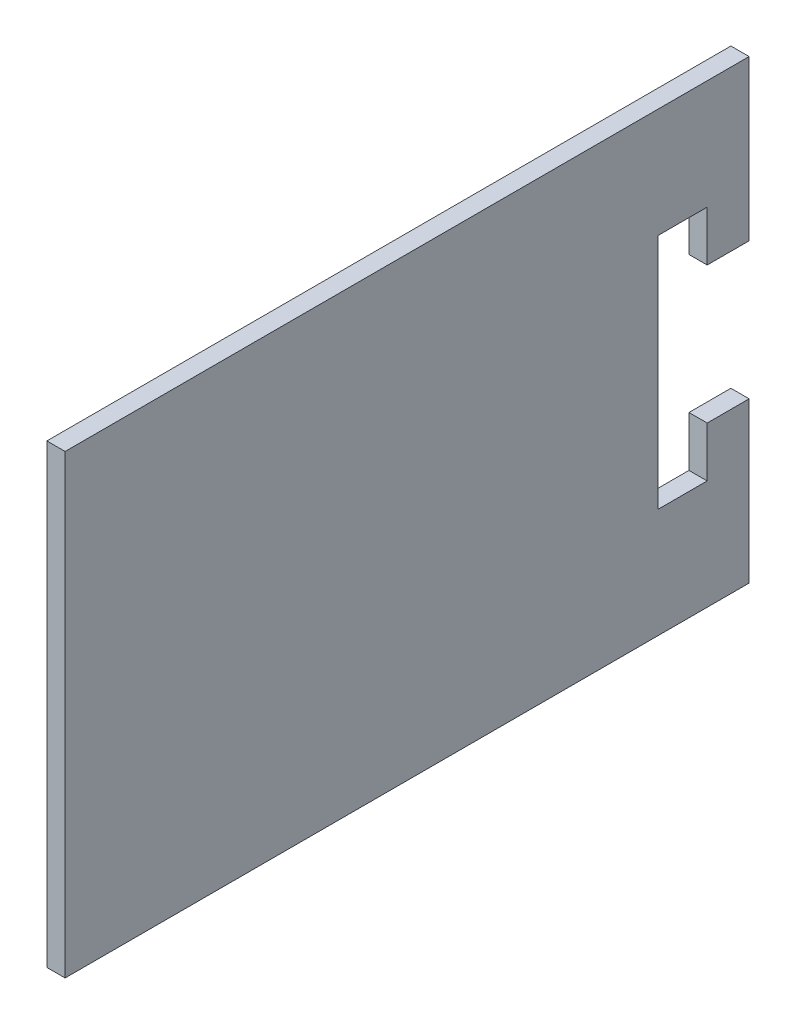
SolidWorks part; units mm, degrees
ref_plane "Front Plane" through (0, 0, 0) normal (1, 0, 0) x (0, 1, 0)
ref_plane "Top Plane" through (0, 0, 0) normal (0, 0, 1) x (0, 1, 0)
ref_plane "Right Plane" through (0, 0, 0) normal (0, 1, 0) x (-1, 0, 0)
sketch "Sketch1" plane through (0, 0, 0) normal (1, 0, 0) x (0, 1, 0)
  line L1 (0, 0) -> (63.5, 0)
  line L2 (0, 0) -> (0, 95.25)
  line L3 (0, 95.25) -> (63.5, 95.25)
  line L4 (63.5, 0) -> (63.5, 95.25)
  dimension "D1" = 95.25
  dimension "D2" = 63.5
extrude "Boss-Extrude1" add sketch "Sketch1" along normal blind 2.54
sketch "Sketch4" plane through (2.54, 0, 0) normal (1, 0, 0) x (0, 1, 0)
  line L0 (0, 95.25) -> (0, 0) construction
  line L1 (0, 0) -> (63.5, 0) construction
  line L2 (63.5, 0) -> (63.5, 95.25) construction
  line L5 (22.225, 0) -> (41.275, 0)
  line L6 (22.225, 0) -> (22.225, 5.842)
  line L7 (22.098, 12.7) -> (41.402, 12.7)
  line L8 (41.275, 0) -> (41.275, 5.842)
  line L9 (22.098, 12.7) -> (15.24, 12.7)
  line L11 (22.225, 5.842) -> (15.24, 5.842)
  line L12 (15.24, 12.7) -> (15.24, 5.842)
  line L13 (41.402, 12.7) -> (48.26, 12.7)
  line L15 (41.275, 5.842) -> (48.26, 5.842)
  line L16 (48.26, 12.7) -> (48.26, 5.842)
  dimension "D1" = 15.24
  dimension "D2" = 15.24
  dimension "D4" = 6.858
  dimension "D5" = 6.858
  dimension "D6" = 6.858
  dimension "D7" = 6.858
extrude "Cut-Extrude1" cut sketch "Sketch4" against normal blind 13.97
sketch "Sketch5" plane through (0, 0, 0) normal (-1, 0, 0) x (0, -1, 0)
  line L0 (-15.24, 12.7) -> (-48.26, 12.7) construction
  line L1 (-40.64, 12.7) -> (-25.4, 12.7)
  line L2 (-40.64, 12.7) -> (-40.64, 27.94)
  line L3 (-40.64, 27.94) -> (-25.4, 27.94)
  line L4 (-25.4, 12.7) -> (-25.4, 27.94)
  line L5 (-63.5, 0) -> (-63.5, 95.25) construction
  dimension "D1" = 15.24
  dimension "D2" = 15.24
  dimension "D3" = 22.86
extrude "Boss-Extrude2" add sketch "Sketch5" along normal blind 15.24
sketch "Sketch6" plane through (0, 0, 12.7) normal (0, 0, -1) x (1, 0, 0)
  line L0 (-15.24, -40.64) -> (0, -40.64) construction
  line L6 (-12.7, -38.1) -> (0, -38.1)
  line L7 (-12.7, -38.1) -> (-12.7, -27.94)
  line L8 (-12.7, -27.94) -> (0, -27.94)
  line L9 (0, -38.1) -> (0, -27.94)
  line L10 (-15.24, -40.64) -> (-15.24, -25.4) construction
  dimension "D1" = 10.16
  dimension "D2" = 12.7
  dimension "D3" = 2.54
  dimension "D4" = 2.54
extrude "Cut-Extrude2" cut sketch "Sketch6" against normal blind 12.7
